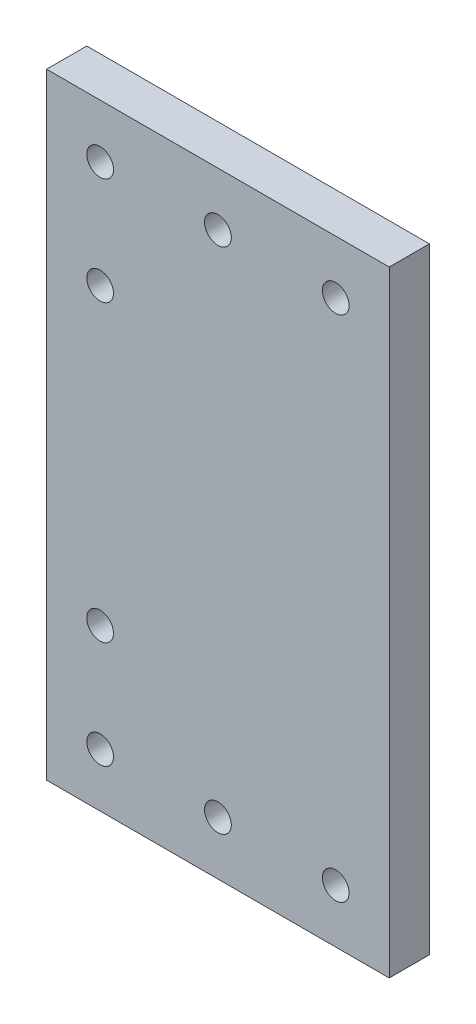
SolidWorks part; units mm, degrees
ref_plane "Front" through (0, 0, 0) normal (0, 0, 1) x (1, 0, 0)
ref_plane "Top" through (0, 0, 0) normal (0, 1, 0) x (1, 0, 0)
ref_plane "Right" through (0, 0, 0) normal (1, 0, 0) x (0, 0, -1)
sketch "Sketch1" plane through (0, 0, 0) normal (0, 0, 1) x (1, 0, 0)
  line L1 (32, -57.5) -> (-32, -57.5)
  line L2 (32, -57.5) -> (32, 57.5)
  line L3 (32, 57.5) -> (-32, 57.5)
  line L4 (-32, -57.5) -> (-32, 57.5)
  line L5 (32, -57.5) -> (-32, 57.5) construction
  line L6 (32, 57.5) -> (-32, -57.5) construction
  point P0 (0, 0)
  dimension "D1" = 64
  dimension "D2" = 115
extrude "Boss-Extrude1" add sketch "Sketch1" along normal mid plane 7.5
sketch "Sketch2" plane through (0, 0, 3.75) normal (0, 0, 1) x (1, 0, 0)
  line L0 (-22, 47.5) -> (-22, 57.5) construction
  line L1 (32, 57.5) -> (-32, 57.5) construction
  line L2 (-22, 47.5) -> (-32, 47.5) construction
  line L3 (-32, 57.5) -> (-32, -57.5) construction
  line L4 (22, 47.5) -> (-22, 47.5) construction
  line L5 (32, -57.5) -> (32, 57.5) construction
  circle A0 centre (-22, 47.5) radius 2.5
  circle A1 centre (0, 47.5) radius 2.5
  circle A2 centre (22, 47.5) radius 2.5
  circle A3 centre (-22, 27.5) radius 2.5
  dimension "D1" = 5
  dimension "D2" = 10
  dimension "D3" = 10
  dimension "D4" = 10
  dimension "D5" = 20
extrude "Cut-Extrude1" cut sketch "Sketch2" against normal through all both and the other way through all
mirror "Mirror1" about plane through (0, 0, 0) normal (0, 1, 0) of "Cut-Extrude1"
